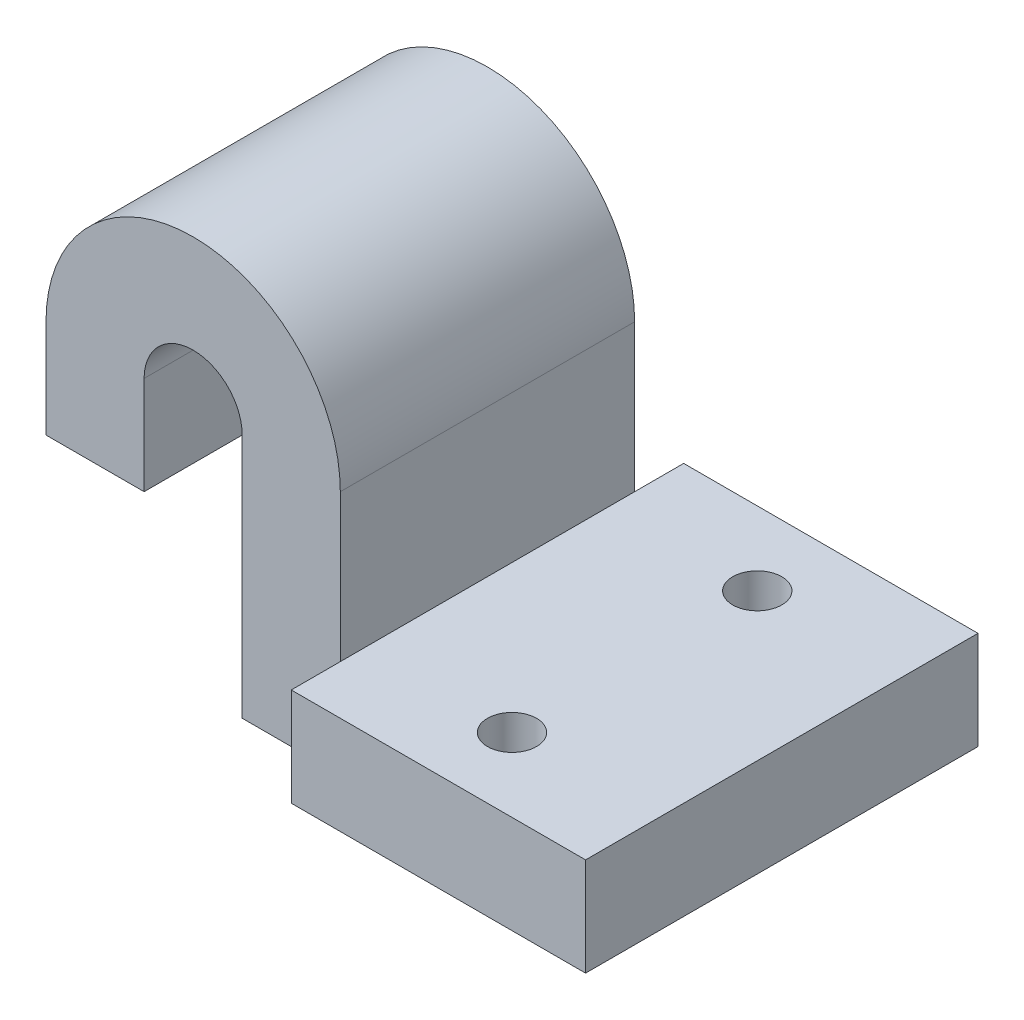
SolidWorks part; units mm, degrees
ref_plane "Front Plane" through (0, 0, 0) normal (0, 0, 1) x (1, 0, 0)
ref_plane "Top Plane" through (0, 0, 0) normal (0, 1, 0) x (1, 0, 0)
ref_plane "Right Plane" through (0, 0, 0) normal (1, 0, 0) x (0, 0, -1)
sketch "Sketch1" plane through (0, 0, 0) normal (0, 1, 0) x (1, 0, 0)
  line L0 (19.05, -9.525) -> (19.05, -15.875) construction
  line L1 (-19.05, 9.525) -> (19.05, 9.525)
  line L2 (-19.05, 9.525) -> (-19.05, -9.525)
  line L3 (-19.05, -9.525) -> (19.05, -9.525)
  line L4 (19.05, 9.525) -> (19.05, -9.525)
  line L5 (-19.05, 9.525) -> (19.05, -9.525) construction
  line L6 (-19.05, -9.525) -> (19.05, 9.525) construction
  line L7 (19.05, -15.875) -> (-19.05, -15.875) construction
  line L8 (-19.05, -41.275) -> (-19.05, -22.225)
  line L9 (-19.05, -22.225) -> (19.05, -22.225)
  line L10 (19.05, -41.275) -> (19.05, -22.225)
  line L11 (-19.05, -41.275) -> (19.05, -41.275)
  line L13 (-19.05, -9.525) -> (19.05, -9.525)
  line L14 (-19.05, -9.525) -> (-19.05, -22.225)
  line L15 (-19.05, -22.225) -> (19.05, -22.225)
  line L16 (19.05, -9.525) -> (19.05, -22.225)
  line L17 (-19.05, -9.525) -> (19.05, -22.225) construction
  line L18 (-19.05, -22.225) -> (19.05, -9.525) construction
  circle A0 centre (0, 0) radius 3.175
  circle A1 centre (0, -31.75) radius 3.175
  point P0 (0, 0)
  point P17 (0, -15.875)
  dimension "D3" = 6.35
  dimension "D1" = 38.1
  dimension "D2" = 19.05
  dimension "D4" = 6.35
extrude "Boss-Extrude2" add sketch "Sketch1" along normal blind 12.7 contours L4 L1 L2 L3 A0 | L16 L3 L14 L9 | L8 L11 L10 L9 A1
ref_plane "Plane1" through (0, 0, 34.925) normal (0, 0, 1) x (1, 0, 0)
sketch "Sketch3" plane through (0, 0, 34.925) normal (0, 0, 1) x (1, 0, 0)
  line L0 (-19.05, 31.75) -> (-38.1, 31.75) construction
  line L1 (-19.05, 0) -> (-31.75, 0)
  line L2 (-19.05, 0) -> (-19.05, 31.75)
  line L3 (-19.05, 31.75) -> (-31.75, 31.75)
  line L4 (-31.75, 0) -> (-31.75, 31.75)
  line L5 (-19.05, 0) -> (-31.75, 31.75) construction
  line L6 (-19.05, 31.75) -> (-31.75, 0) construction
  line L7 (-26.67, 46.99) -> (19.05, 12.7)
  line L8 (-57.15, 31.75) -> (-44.45, 31.75)
  line L9 (-57.15, 31.75) -> (-57.15, 19.05)
  line L10 (-57.15, 19.05) -> (-44.45, 19.05)
  line L11 (-44.45, 31.75) -> (-44.45, 19.05)
  line L12 (-57.15, 31.75) -> (-44.45, 19.05) construction
  line L13 (-57.15, 19.05) -> (-44.45, 31.75) construction
  line L14 (-19.05, 12.7) -> (19.05, 12.7) construction
  line L15 (-19.05, 0) -> (19.05, 0) construction
  line L16 (19.05, 12.7) -> (-19.05, 12.7)
  arc A0 (-19.05, 31.75) -> (-57.15, 31.75) centre (-38.1, 31.75) ccw
  arc A1 (-31.75, 31.75) -> (-44.45, 31.75) centre (-38.1, 31.75) ccw
  point P4 (-25.4, 15.875)
  point P11 (-50.8, 25.4)
  dimension "D1" = 12.7
  dimension "D2" = 31.75
  dimension "D3" = 19.05
  dimension "D4" = 12.7
  dimension "D5" = 12.7
  dimension "D6" = 19.05
extrude "Boss-Extrude3" add sketch "Sketch3" against normal blind 38.1 contours A1 L3 A0 L8 | L4 L1 L2 L3 | L11 L8 L9 L10
